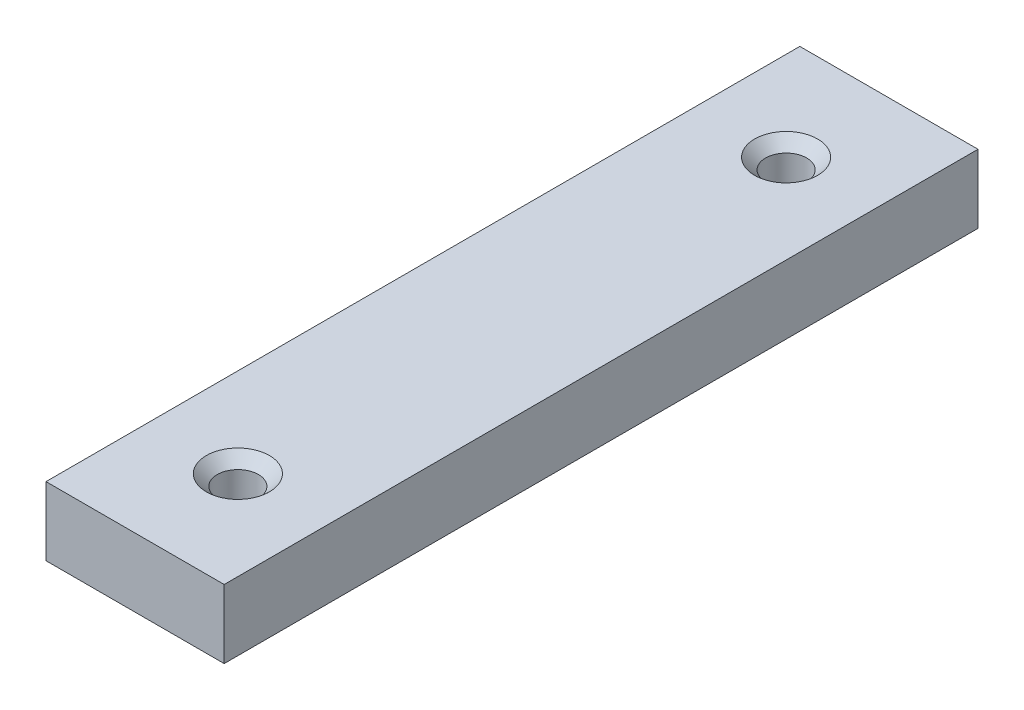
SolidWorks part; units mm, degrees
material "Сталь 08пс ГОСТ 535-88"
ref_plane "Спереди" through (0, 0, 0) normal (0, 0, 1) x (1, 0, 0)
ref_plane "Сверху" through (0, 0, 0) normal (0, 1, 0) x (1, 0, 0)
ref_plane "Справа" through (0, 0, 0) normal (1, 0, 0) x (0, 0, -1)
sketch "Эскиз1" plane through (0, 0, 0) normal (0, 0, 1) x (1, 0, 0)
  line L0 (-34.4035, 28.782) -> (34.4035, -28.782) construction
  line L1 (-34.4035, 28.782) -> (34.4035, 28.782)
  line L2 (-34.4035, 28.782) -> (-34.4035, -28.782)
  line L3 (-34.4035, -28.782) -> (34.4035, -28.782)
  line L4 (34.4035, 28.782) -> (34.4035, -28.782)
sketch "Эскиз2" plane through (0, 0, 0) normal (0, 1, 0) x (1, 0, 0)
  line L1 (-13, -55) -> (13, -55)
  line L2 (-13, -55) -> (-13, 55)
  line L3 (-13, 55) -> (13, 55)
  line L4 (13, -55) -> (13, 55)
  line L5 (-13, -55) -> (13, 55) construction
  line L6 (-13, 55) -> (13, -55) construction
  point P0 (0, 0)
  dimension "D1" = 110
  dimension "D2" = 26
extrude "Бобышка-Вытянуть1" add sketch "Эскиз2" along normal mid plane 10
sketch "Эскиз3" plane through (0, 5, 0) normal (0, 1, 0) x (1, 0, 0)
  line L0 (0, 26.6908) -> (0, -21.4129) construction
  line L1 (-8.3691, 0) -> (10.7819, 0) construction
  circle A0 centre (0, 40) radius 3
  circle A1 centre (0, -40) radius 3
  dimension "D1" = 6
  dimension "D2" = 80
extrude "Вырез-Вытянуть1" cut sketch "Эскиз3" against normal up to next
chamfer "Фаска1" distance 1.6 angle 45 2 edges at (0, 5, 43) (0, 5, -37)
